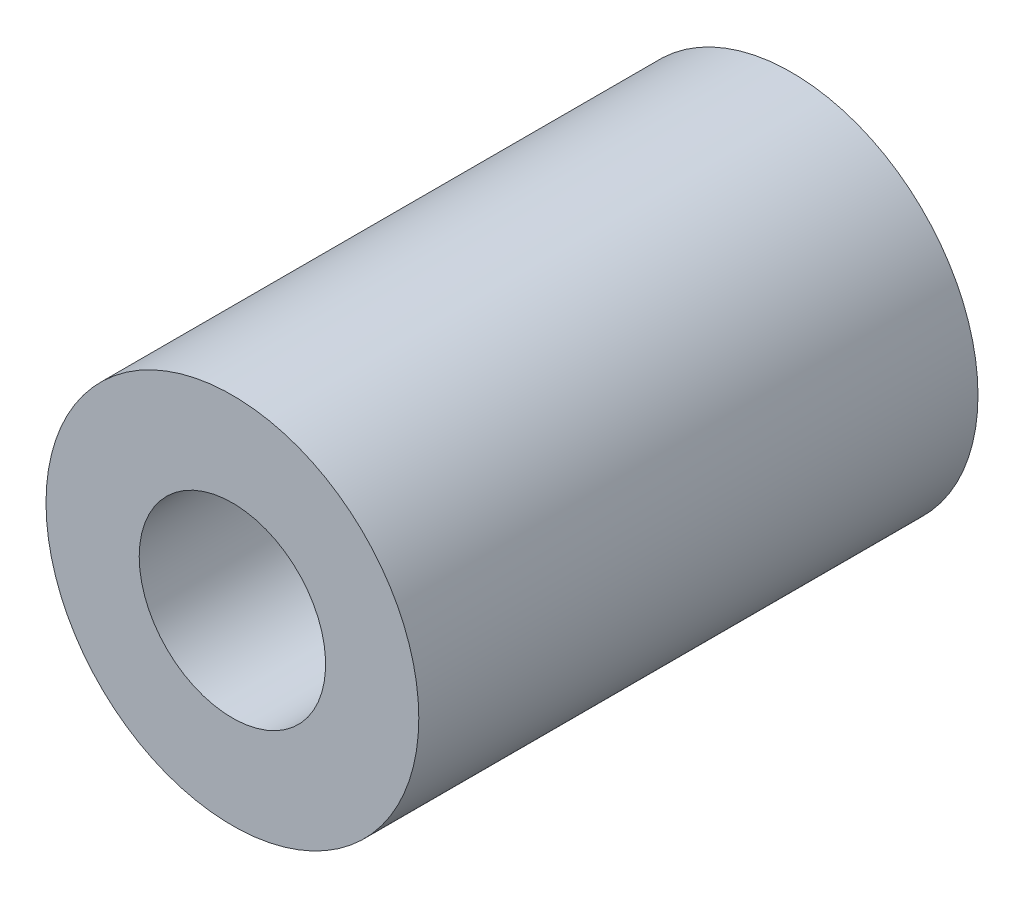
SolidWorks part; units mm, degrees
ref_plane "Front Plane" through (0, 0, 0) normal (0, 0, 1) x (1, 0, 0)
ref_plane "Top Plane" through (0, 0, 0) normal (0, 1, 0) x (1, 0, 0)
ref_plane "Right Plane" through (0, 0, 0) normal (1, 0, 0) x (0, 0, -1)
sketch "Sketch1" plane through (0, 0, 0) normal (0, 0, 1) x (1, 0, 0)
  circle A0 centre (0, 0) radius 6.35
  circle A1 centre (0, 0) radius 3.175
  dimension "D1" = 6.35
  dimension "D2" = 12.7
extrude "Boss-Extrude1" add sketch "Sketch1" along normal mid plane 19.05
